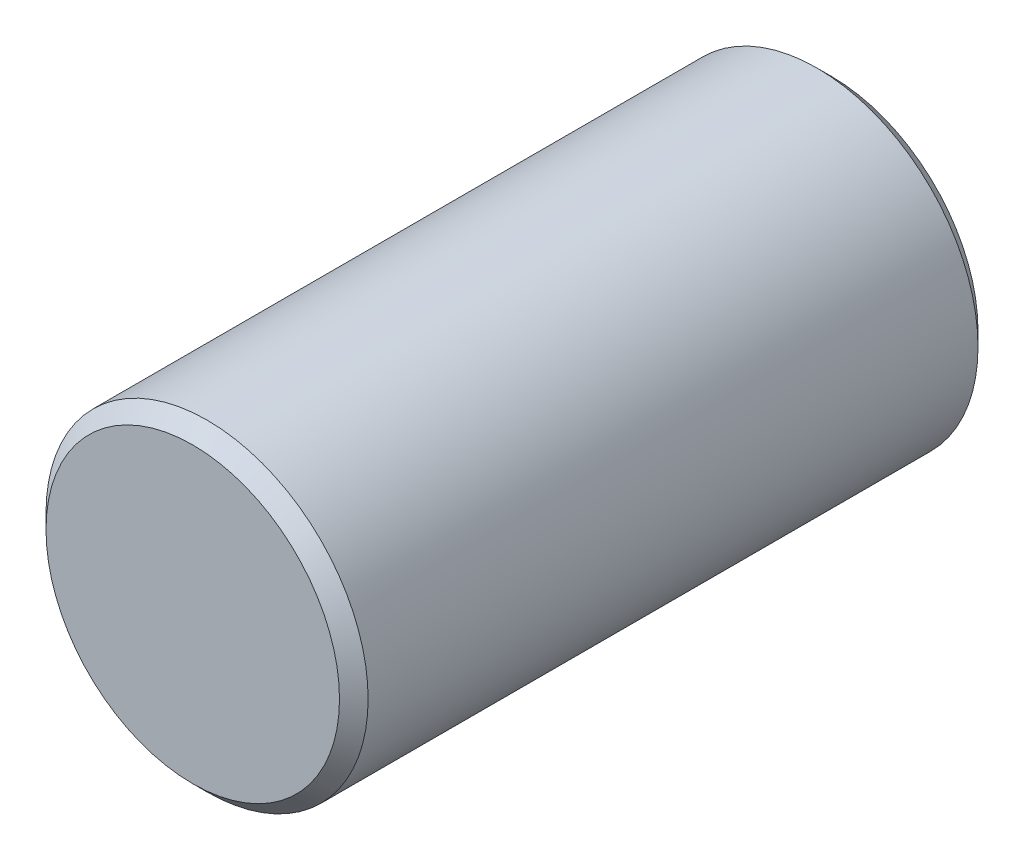
SolidWorks part; units mm, degrees
ref_plane "Plan de face" through (0, 0, 0) normal (0, 0, 1) x (1, 0, 0)
ref_plane "Plan de dessus" through (0, 0, 0) normal (0, 1, 0) x (1, 0, 0)
ref_plane "Plan de droite" through (0, 0, 0) normal (1, 0, 0) x (0, 0, -1)
sketch "Esquisse1" plane through (0, 0, 0) normal (0, 0, 1) x (1, 0, 0)
  circle A0 centre (0, 0) radius 11.25
  dimension "D1" = 22.5
extrude "Extrusion1" add sketch "Esquisse1" along normal blind 44.6
chamfer "Chanfrein1" distance 1 angle 45 2 edges at (11.25, 0, 44.6) (11.25, 0, 0)
